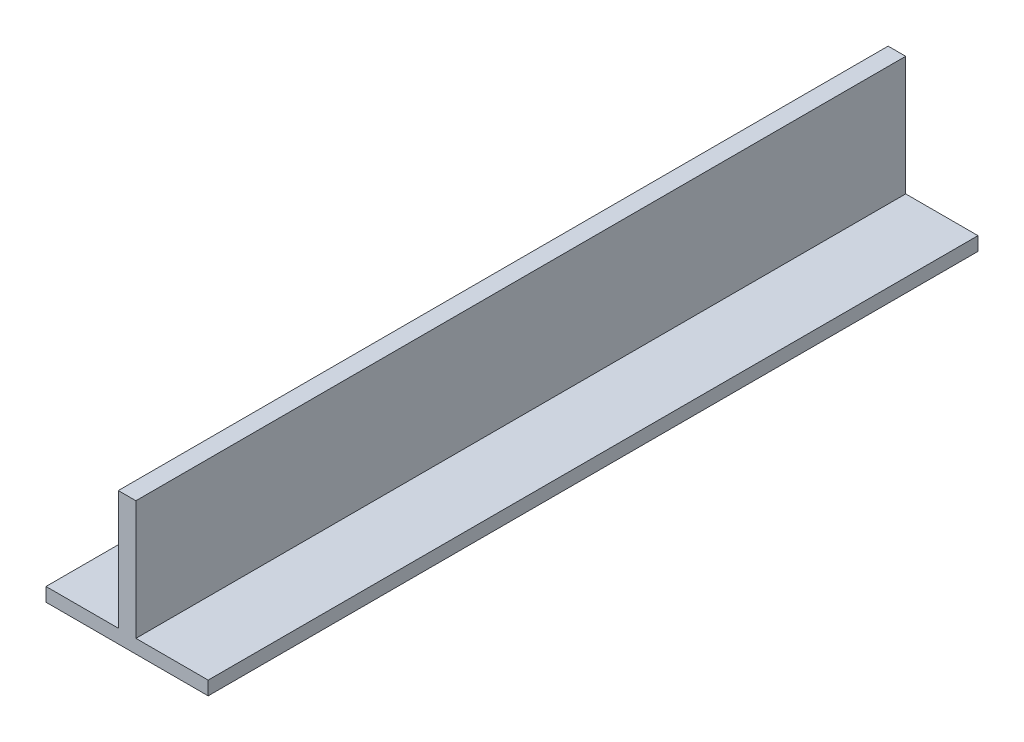
SolidWorks part; units mm, degrees
ref_plane "Plan de face" through (0, 0, 0) normal (0, 0, 1) x (1, 0, 0)
ref_plane "Plan de dessus" through (0, 0, 0) normal (0, 1, 0) x (1, 0, 0)
ref_plane "Plan de droite" through (0, 0, 0) normal (1, 0, 0) x (0, 0, -1)
sketch "Esquisse1" plane through (0, 0, 0) normal (0, 0, 1) x (1, 0, 0)
  line L0 (0, 0) -> (83, 0)
  line L1 (83, 0) -> (83, 7)
  line L2 (83, 7) -> (46, 7)
  line L3 (46, 7) -> (46, 68)
  line L4 (46, 68) -> (37, 68)
  line L5 (37, 68) -> (37, 7)
  line L6 (37, 7) -> (0, 7)
  line L7 (0, 7) -> (0, 0)
  dimension "D1" = 7
  dimension "D2" = 9
  dimension "D3" = 83
  dimension "D4" = 68
extrude "Boss.-Extru.1" add sketch "Esquisse1" along normal blind 394
